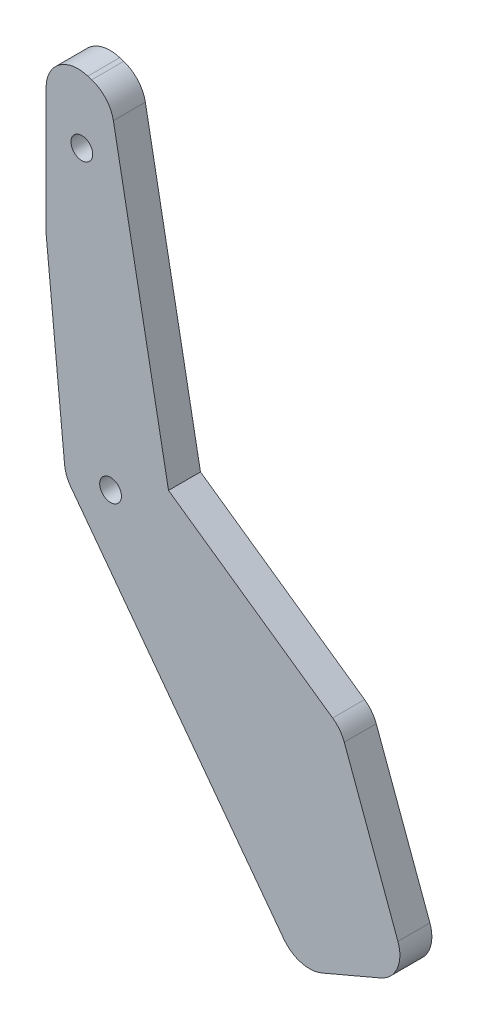
SolidWorks part; units mm, degrees
ref_plane "Front Plane" through (0, 0, 0) normal (0, 0, 1) x (1, 0, 0)
ref_plane "Top Plane" through (0, 0, 0) normal (0, 1, 0) x (1, 0, 0)
ref_plane "Right Plane" through (0, 0, 0) normal (1, 0, 0) x (0, 0, -1)
sketch "Sketch1" plane through (0, 0, 0) normal (0, 0, 1) x (1, 0, 0)
  line L0 (9.5711, 22.2907) -> (12.4589, -7.5497)
  line L1 (13.4307, -10.0615) -> (46.7628, -54.6575)
  line L2 (52.7291, -56.2633) -> (61.868, -52.3658)
  line L3 (64.5983, -46.0381) -> (56.2045, -23.2548)
  line L4 (54.3827, -20.889) -> (28.7134, -2.8965)
  line L5 (28.7134, -2.8965) -> (20.0927, 42.8825)
  line L6 (16.6992, 46.7205) -> (16.0913, 46.9145)
  line L7 (9.5711, 42.1512) -> (9.5711, 22.2907)
  line L8 (19.6487, -7.3641) -> (15.1559, 36.6985) construction
  circle A0 centre (15.1559, 36.6985) radius 1.7
  circle A1 centre (19.6487, -7.3641) radius 1.7
  arc A2 (12.4589, -7.5497) -> (13.4307, -10.0615) centre (17.4357, -7.0681) ccw
  arc A3 (46.7628, -54.6575) -> (52.7291, -56.2633) centre (50.7677, -51.6641) ccw
  arc A4 (61.868, -52.3658) -> (64.5983, -46.0381) centre (59.9066, -47.7666) ccw
  arc A5 (56.2045, -23.2548) -> (54.3827, -20.889) centre (51.5128, -24.9834) ccw
  arc A6 (20.0927, 42.8825) -> (16.6992, 46.7205) centre (15.179, 41.9572) ccw
  arc A7 (16.0913, 46.9145) -> (9.5711, 42.1512) centre (14.5711, 42.1512) ccw
  dimension "D1" = 5
extrude "Boss-Extrude1" add sketch "Sketch1" along normal blind 5
